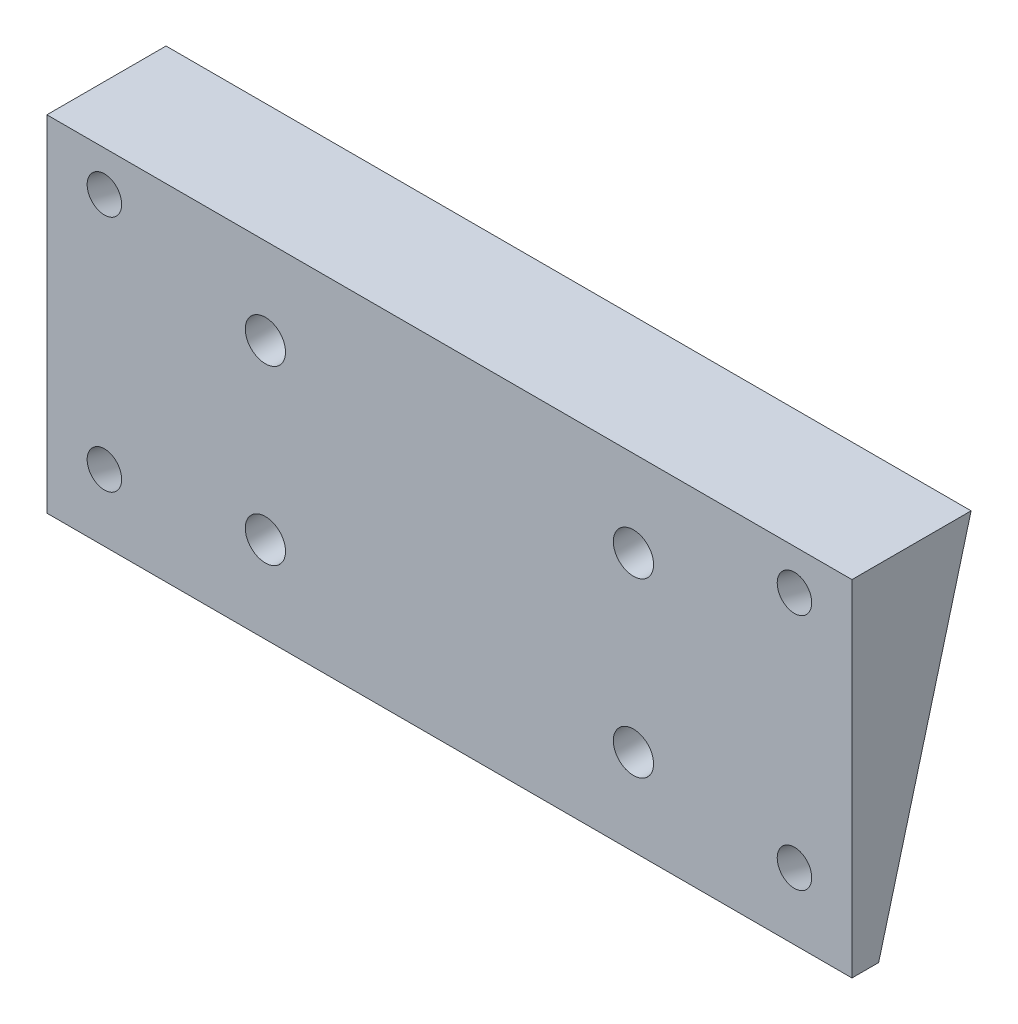
SolidWorks part; units mm, degrees
ref_plane "前视基准面" through (0, 0, 0) normal (0, 0, 1) x (1, 0, 0)
ref_plane "上视基准面" through (0, 0, 0) normal (0, 1, 0) x (1, 0, 0)
ref_plane "右视基准面" through (0, 0, 0) normal (1, 0, 0) x (0, 0, -1)
sketch "草图1" plane through (0, 0, 0) normal (0, 0, 1) x (1, 0, 0)
  line L3 (74.641, 0) -> (74.641, 20)
  line L4 (74.641, 0) -> (34.641, 0)
  line L5 (34.641, 0) -> (34.641, 9.282)
  line L6 (74.641, 20) -> (34.641, 20)
  line L7 (34.641, 20) -> (34.641, 9.282)
  dimension "D3" = 40
extrude "凸台-拉伸1" add sketch "草图1" along normal blind 40
sketch "草图8" plane through (74.641, 0, 0) normal (1, 0, 0) x (0, 0, -1)
  line L0 (0, 0) -> (0, 20)
  line L1 (0, 0) -> (5.359, 20)
  line L2 (0, 20) -> (5.359, 20)
  dimension "D1" = 15
extrude "凸台-拉伸2" add sketch "草图8" against normal blind 40
sketch "草图9" plane through (0, 0, 40) normal (0, 0, 1) x (1, 0, 0)
  line L0 (54.641, 20) -> (54.641, 0) construction
  line L1 (74.641, 20) -> (34.641, 20) construction
  line L2 (34.641, 0) -> (74.641, 0) construction
  line L4 (44.391, 0) -> (64.891, 0)
  line L5 (44.391, 0) -> (44.391, 20)
  line L6 (44.391, 20) -> (64.891, 20)
  line L7 (64.891, 0) -> (64.891, 20)
  line L8 (44.391, 0) -> (64.891, 20) construction
  line L9 (44.391, 20) -> (64.891, 0) construction
  point P6 (54.641, 10)
  dimension "D1" = 20
  dimension "D2" = 20.5
extrude "切除-拉伸2" cut sketch "草图9" against normal blind 20
sketch "草图10" plane through (0, 0, 40) normal (0, 0, 1) x (1, 0, 0)
  line L1 (74.641, 20) -> (69.766, 20)
  line L2 (74.641, 20) -> (74.641, 0)
  line L3 (74.641, 0) -> (69.766, 0)
  line L4 (69.766, 20) -> (69.766, 0)
  line L5 (64.891, 0) -> (74.641, 0) construction
  line L7 (34.641, 20) -> (39.516, 20)
  line L8 (34.641, 20) -> (34.641, 0)
  line L9 (34.641, 0) -> (39.516, 0)
  line L10 (39.516, 20) -> (39.516, 0)
  line L11 (34.641, 0) -> (44.391, 0) construction
  dimension "D1" = 20
  dimension "D2" = 4.875
  dimension "D3" = 20
  dimension "D4" = 4.875
extrude "切除-拉伸3" cut sketch "草图10" against normal blind 20
sketch "草图11" plane through (74.641, 0, 0) normal (1, 0, 0) x (0, 0, -1)
  line L0 (0, 0) -> (5.359, 20) construction
  line L1 (0, 0) -> (5.359, 20)
  line L2 (0, 0) -> (-15, 0) construction
  line L3 (-20, 0) -> (0, 0) construction
  line L4 (-15, 0) -> (-9.641, 20)
  line L5 (5.359, 20) -> (-9.641, 20)
  line L6 (-20, 20) -> (5.359, 20) construction
  line L7 (0, 0) -> (-15, 0)
  dimension "D1" = 15
extrude "切除-拉伸4" cut sketch "草图11" against normal blind 55
sketch "草图12" plane through (0, 0, 20) normal (0, 0, 1) x (1, 0, 0)
  line L1 (30.1657, 26.0564) -> (81.8225, 26.0564)
  line L2 (30.1657, 26.0564) -> (30.1657, -8.161)
  line L3 (30.1657, -8.161) -> (81.8225, -8.161)
  line L4 (81.8225, 26.0564) -> (81.8225, -8.161)
extrude "切除-拉伸5" cut sketch "草图12" along normal blind 34
sketch "草图15" plane through (34.641, 0, 0) normal (-1, 0, 0) x (0, 0, 1)
  line L0 (20, 0) -> (20, -10)
  line L1 (20, 0) -> (15, 0)
  line L2 (15, 0) -> (17.6795, -10)
  line L3 (17.6795, -10) -> (20, -10)
  dimension "D1" = 10
extrude "凸台-拉伸3" add sketch "草图15" against normal blind 40
sketch "草图16" plane through (0, 0, 20) normal (0, 0, 1) x (1, 0, 0)
  line L0 (34.641, 5) -> (74.641, 5) construction
  line L1 (34.641, 20) -> (34.641, -10) construction
  line L2 (74.641, -10) -> (74.641, 20) construction
  line L4 (38.641, -2.5) -> (70.641, -2.5) construction
  line L5 (38.641, -2.5) -> (38.641, 12.5) construction
  line L6 (38.641, 12.5) -> (70.641, 12.5) construction
  line L7 (70.641, -2.5) -> (70.641, 12.5) construction
  line L8 (38.641, -2.5) -> (70.641, 12.5) construction
  line L9 (38.641, 12.5) -> (70.641, -2.5) construction
  circle A0 centre (38.641, 12.5) radius 1.75
  circle A1 centre (70.641, 12.5) radius 1.75
  circle A2 centre (70.641, -2.5) radius 1.75
  circle A3 centre (38.641, -2.5) radius 1.75
  point P6 (54.641, 5)
  dimension "D3" = 3.5
  dimension "D4" = 3.5
  dimension "D5" = 3.5
  dimension "D6" = 3.5
  dimension "D1" = 15
  dimension "D2" = 32
extrude "切除-拉伸6" cut sketch "草图16" against normal blind 10
sketch "草图17" plane through (74.641, 0, 0) normal (1, 0, 0) x (0, 0, -1)
  line L4 (-20, 20) -> (-20, -10)
  line L5 (-20, -10) -> (-17.6795, -10)
  line L6 (-17.6795, -10) -> (-9.641, 20)
  line L7 (-9.641, 20) -> (-20, 20)
  line L8 (-20, 20) -> (-20, -10)
  line L9 (-20, -10) -> (-17.6795, -10)
  line L10 (-17.6795, -10) -> (-9.641, 20)
  line L11 (-9.641, 20) -> (-20, 20)
  dimension "D1" = 0
extrude "凸台-拉伸4" add sketch "草图17" along normal blind 15
sketch "草图18" plane through (34.641, 0, 0) normal (-1, 0, 0) x (0, 0, 1)
  line L4 (20, 20) -> (9.641, 20)
  line L5 (9.641, 20) -> (17.6795, -10)
  line L6 (17.6795, -10) -> (20, -10)
  line L7 (20, -10) -> (20, 20)
  line L8 (20, 20) -> (9.641, 20)
  line L9 (9.641, 20) -> (17.6795, -10)
  line L10 (17.6795, -10) -> (20, -10)
  line L11 (20, -10) -> (20, 20)
  dimension "D1" = 0
extrude "凸台-拉伸5" add sketch "草图18" along normal blind 15
sketch "草图19" plane through (0, 3.75, 13.9952) normal (0, -0.2588, -0.9659) x (-1, 0, 0)
  circle A4 centre (-84.641, -9.235) radius 1.5
  circle A5 centre (-84.641, 10.765) radius 1.5
  circle A6 centre (-24.641, -9.235) radius 1.5
  circle A7 centre (-24.641, 10.765) radius 1.5
extrude "切除-拉伸7" cut sketch "草图19" against normal blind 10
